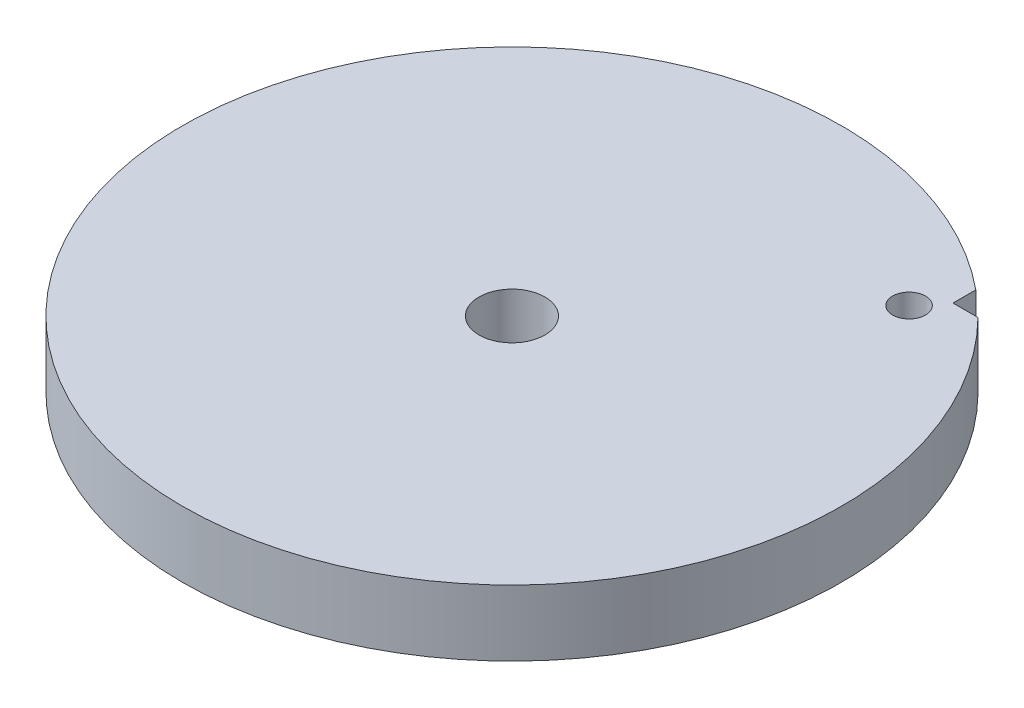
SolidWorks part; units mm, degrees
other "Marcação1"
sketch "Esboço2" plane through (-15, 3, 15) normal (-0.4698, 0.7205, 0.51) x (0.8709, 0.2841, 0.4009)
ref_plane "Plano frontal" through (0, 0, 0) normal (0, 0, 1) x (1, 0, 0)
ref_plane "Plano superior" through (0, 0, 0) normal (0, 1, 0) x (1, 0, 0)
ref_plane "Plano direito" through (0, 0, 0) normal (1, 0, 0) x (0, 0, -1)
sketch "Esboço1" plane through (0, 0, 0) normal (0, 1, 0) x (1, 0, 0)
  line L0 (9.5275, 11.5856) -> (9.5275, 10.5468)
  line L1 (9.5275, 10.5468) -> (10.666, 10.5468)
  arc A0 (9.5275, 11.5856) -> (10.666, 10.5468) centre (0, 0) ccw
  circle A1 centre (0, 0) radius 1.5
  circle A2 centre (8.6259, 9.4492) radius 0.75
  dimension "D1" = 30
  dimension "D2" = 3
  dimension "D3" = 1.5
extrude "Ressalto-extrusão1" add sketch "Esboço1" along normal blind 3
